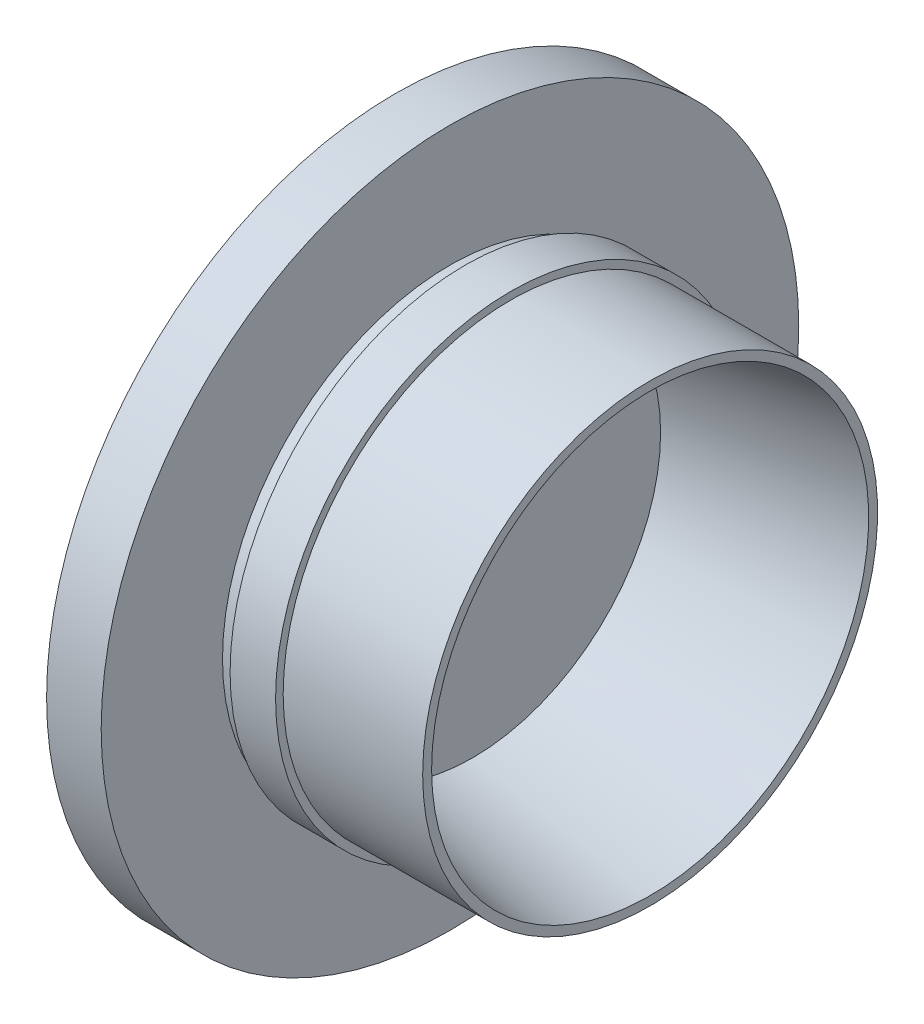
SolidWorks part; units mm, degrees
ref_plane "前视基准面" through (0, 0, 0) normal (0, 0, 1) x (1, 0, 0)
ref_plane "上视基准面" through (0, 0, 0) normal (0, 1, 0) x (1, 0, 0)
ref_plane "右视基准面" through (0, 0, 0) normal (1, 0, 0) x (0, 0, -1)
sketch "草图1" plane through (0, 0, 0) normal (0, 0, 1) x (1, 0, 0)
  line L0 (1, 30) -> (1, 17)
  line L1 (0, 30) -> (0, 46)
  line L2 (10.2, 0) -> (33.6, 0)
  line L3 (1, 30) -> (0, 30)
  line L4 (1, 17) -> (1, 0)
  line L5 (0, 46) -> (7.2, 46)
  line L6 (7.2, 46) -> (7.2, 30)
  line L7 (7.2, 30) -> (9.2, 30)
  line L8 (9.2, 30) -> (9.2, 31)
  line L9 (9.2, 31) -> (15.2, 31)
  line L10 (15.2, 31) -> (15.2, 30)
  line L11 (15.2, 30) -> (33.6, 30)
  line L12 (10.2, 17) -> (10.2, 0)
  line L15 (10.2, 17) -> (10.2, 24.78)
  line L16 (33.6, 30) -> (33.6, 28.8226)
  line L17 (10.2, 24.78) -> (33.6, 28.8226)
  line L21 (0, 0) -> (10.2, 0)
revolve "旋转1" add sketch "草图1" angle 360 about L21
